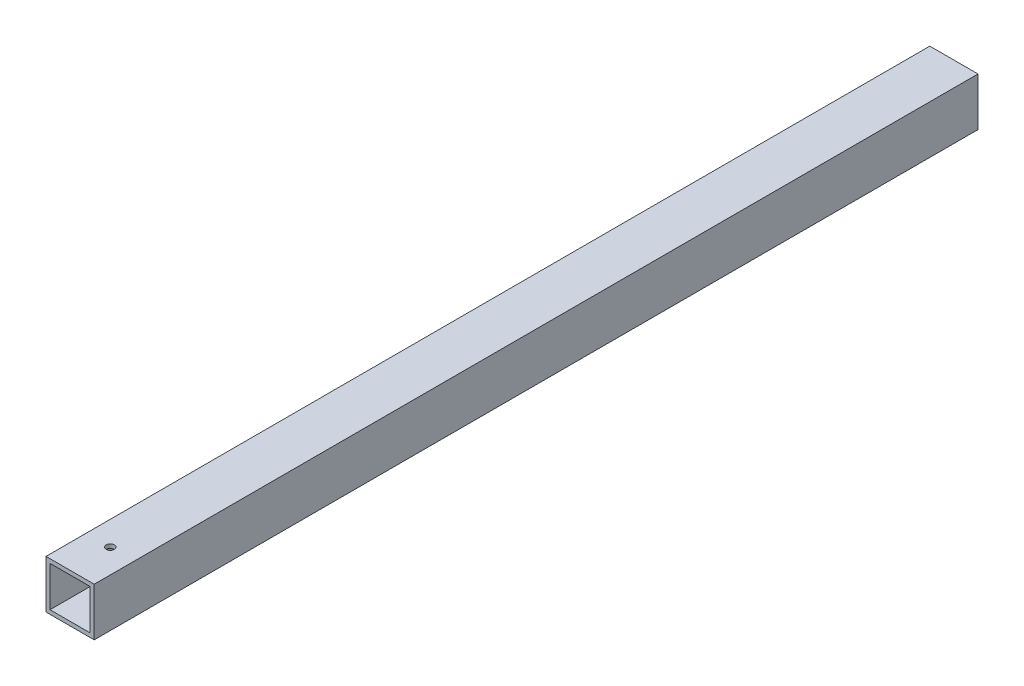
SolidWorks part; units mm, degrees
ref_plane "前视基准面" through (0, 0, 0) normal (0, 0, 1) x (1, 0, 0)
ref_plane "上视基准面" through (0, 0, 0) normal (0, 1, 0) x (1, 0, 0)
ref_plane "右视基准面" through (0, 0, 0) normal (1, 0, 0) x (0, 0, -1)
sketch "草图1" plane through (0, 0, 0) normal (0, 0, 1) x (1, 0, 0)
  line L1 (0, 0) -> (12, 0)
  line L2 (0, 0) -> (0, 12)
  line L3 (0, 12) -> (12, 12)
  line L4 (12, 0) -> (12, 12)
  line L5 (1, 1) -> (11, 1)
  line L6 (1, 1) -> (1, 11)
  line L7 (1, 11) -> (11, 11)
  line L8 (11, 1) -> (11, 11)
  point P5 (1, 1)
extrude "凸台-拉伸1" add sketch "草图1" along normal blind 220.0023
sketch "草图2" plane through (0, 0, 0) normal (0, -1, 0) x (1, 0, 0)
  circle A0 centre (6, 210.0023) radius 1
  point P0 (6, 210.0023)
  point P3 (0, 0)
extrude "切除-拉伸1" cut sketch "草图2" against normal blind 12
